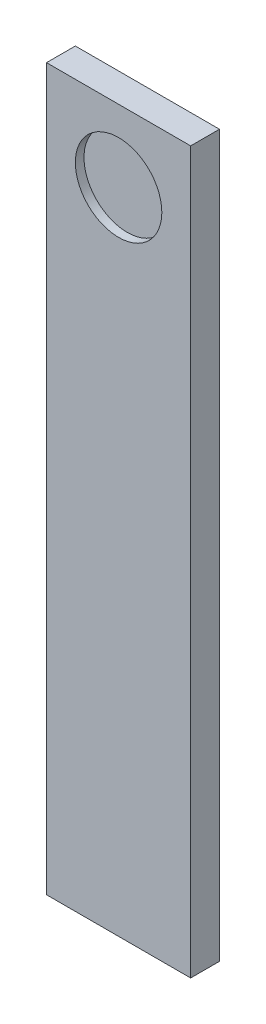
SolidWorks part; units mm, degrees
material "Plain Carbon Steel"
ref_plane "Front Plane" through (0, 0, 0) normal (0, 0, 1) x (1, 0, 0)
ref_plane "Top Plane" through (0, 0, 0) normal (0, 1, 0) x (1, 0, 0)
ref_plane "Right Plane" through (0, 0, 0) normal (1, 0, 0) x (0, 0, -1)
sketch "Sketch1" plane through (0, 0, 0) normal (0, 0, 1) x (1, 0, 0)
  line L1 (-25, 125) -> (25, 125)
  line L2 (-25, 125) -> (-25, -125)
  line L3 (-25, -125) -> (25, -125)
  line L4 (25, 125) -> (25, -125)
  line L5 (-25, 125) -> (25, -125) construction
  line L6 (-25, -125) -> (25, 125) construction
  point P0 (0, 0)
  dimension "D1" = 50
  dimension "D2" = 250
extrude "Boss-Extrude1" add sketch "Sketch1" along normal mid plane 10
sketch "Sketch2" plane through (0, 0, 5) normal (0, 0, 1) x (1, 0, 0)
  line L0 (25, 125) -> (-25, 125) construction
  circle A0 centre (0, 100) radius 15
  dimension "D1" = 25
  dimension "D4" = 30
extrude "Cut-Extrude1" cut sketch "Sketch2" against normal blind 3
sketch "Sketch5" plane through (0, 0, -5) normal (0, 0, -1) x (-1, 0, 0)
  line L0 (25, -125) -> (-25, -125) construction
  circle A0 centre (0, -100) radius 15
  dimension "D2" = 30
  dimension "D1" = 25
extrude "Cut-Extrude2" cut sketch "Sketch5" against normal blind 3
sketch "Sketch6" plane through (0, 0, -2) normal (0, 0, -1) x (-1, 0, 0)
  point P0 (0, -100)
sketch "Sketch7" plane through (0, 0, 2) normal (0, 0, 1) x (1, 0, 0)
  point P0 (0, 100)
